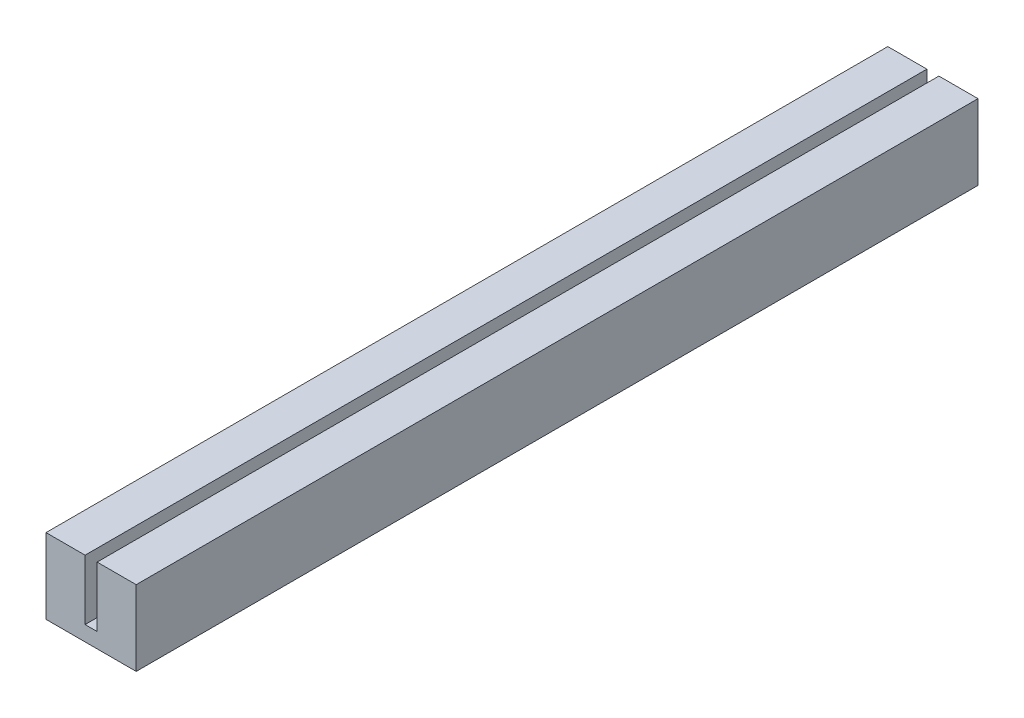
SolidWorks part; units mm, degrees
ref_plane "前视基准面" through (0, 0, 0) normal (0, 0, 1) x (1, 0, 0)
ref_plane "上视基准面" through (0, 0, 0) normal (0, 1, 0) x (1, 0, 0)
ref_plane "右视基准面" through (0, 0, 0) normal (1, 0, 0) x (0, 0, -1)
other "Configuration Table"
sketch "草图1" plane through (0, 0, 0) normal (0, 1, 0) x (1, 0, 0)
  line L1 (0, 46.6541) -> (30, 46.6541)
  line L2 (0, 46.6541) -> (0, -233.3459)
  line L3 (0, -233.3459) -> (30, -233.3459)
  line L4 (30, 46.6541) -> (30, -233.3459)
  dimension "D1" = 280
  dimension "D2" = 30
extrude "凸台-拉伸1" add sketch "草图1" against normal blind 5
sketch "草图2" plane through (0, 0, 0) normal (0, 1, 0) x (1, 0, 0)
  line L7 (0, 46.6541) -> (13, 46.6541)
  line L8 (0, 46.6541) -> (0, -233.3459)
  line L9 (0, -233.3459) -> (13, -233.3459)
  line L10 (13, 46.6541) -> (13, -233.3459)
  line L11 (30, 46.6541) -> (17, 46.6541)
  line L12 (30, 46.6541) -> (30, -233.3459)
  line L13 (30, -233.3459) -> (17, -233.3459)
  line L14 (17, 46.6541) -> (17, -233.3459)
  dimension "D1" = 280
  dimension "D2" = 13
  dimension "D3" = 280
  dimension "D4" = 13
extrude "凸台-拉伸2" add sketch "草图2" along normal blind 20
